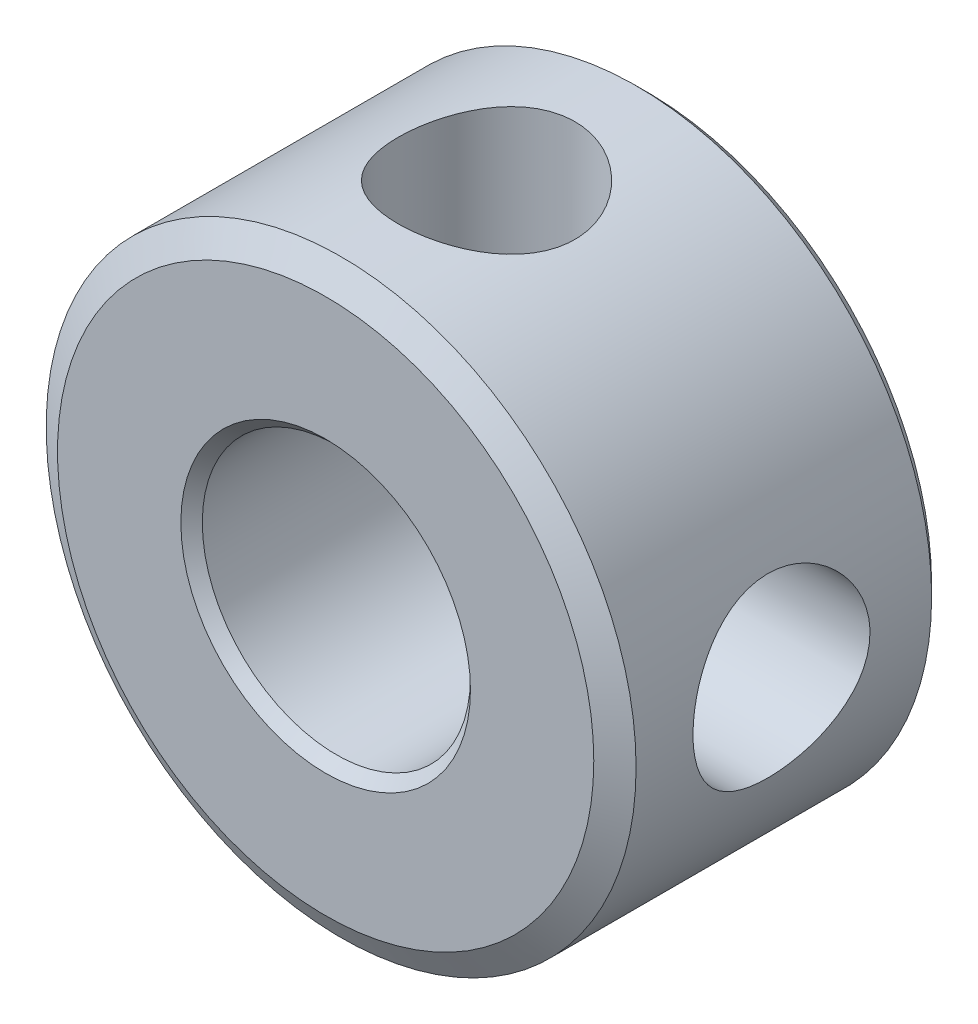
SolidWorks part; units mm, degrees
ref_plane "Front Plane" through (0, 0, 0) normal (0, 0, 1) x (1, 0, 0)
ref_plane "Top Plane" through (0, 0, 0) normal (0, 1, 0) x (1, 0, 0)
ref_plane "Right Plane" through (0, 0, 0) normal (1, 0, 0) x (0, 0, -1)
sketch "Sketch1" plane through (0, 0, 0) normal (1, 0, 0) x (0, 0, -1)
  line L0 (0, 0) -> (6, 0) construction
  line L1 (0, 5.5) -> (6, 5.5)
  line L3 (0, 2.5) -> (6, 2.5)
  line L4 (6, 5.5) -> (6, 2.5)
  line L5 (0, 2.5) -> (0, 5.5)
  dimension "D" = 5
  dimension "D1." = 11
  dimension "B" = 6
revolve "Revolve1" add sketch "Sketch1" angle 360 about L0
ref_plane "Plane1" through (0, 5.5, 0) normal (0, 1, 0) x (1, 0, 0)
hole_wizard "Tapped Hole1" positions "Sketch3" profile "Sketch2" tap size "M4x0.7" standard "JIS"
sketch "Sketch3" plane through (0, 5.5, 0) normal (0, 1, 0) x (1, 0, 0)
  line L2 (5.5, 6) -> (-5.5, 6) construction
  point P0 (0, 3)
sketch "Sketch2" plane through (0, 5.5, -3) normal (1, 0, 0) x (0, 0, 1)
  line L0 (0, 0) -> (0, 3)
  line L1 (0, 3) -> (1.65, 3)
  line L2 (1.65, 3) -> (1.65, 0)
  line L5 (1.65, 0) -> (0, 0)
  line L11 (0, 0) -> (0, 3) construction
  dimension "Thru Tap Drill Dia." = 3.3
  dimension "Thru Tap Drill Depth" = 3
cosmetic thread "Hole Thread2" parameters "M"=4
pattern_circular "CirPattern1" count 2 every 90 about axis through (0, 0, 0) along (0, 0, 1) of "Tapped Hole1"
chamfer "Chamfer1" distance 0.2 3 edges at (5.5, 0, -6) (2.5, 0, 0) (2.5, 0, -6)
sketch "Sketch4" plane through (0, 0, 0) normal (1, 0, 0) x (0, 0, -1)
  line L1 (0.2887, 5.5) -> (0, 5)
  line L3 (0, 5.5) -> (6, 5.5) construction
  line L4 (0.2887, 5.5) -> (0, 5.5)
  line L5 (0, 0) -> (6, 0) construction
  line L6 (6, -5.5) -> (6, 5.5) construction
  line L7 (0, 2.5) -> (0, 5.5) construction
  line L8 (0, 5.5) -> (0, 5)
  dimension "D1_s" = 10
  dimension "D1" = 30
revolve "Cut-Revolve1" cut sketch "Sketch4" angle 360 about L5
sketch "Sketch5" [suppressed] plane through (0, 0, 0) normal (1, 0, 0) x (0, 0, -1)
  line L0 (0, 5.5) -> (0, 5)
  line L1 (0, 5.5) -> (0, -5.5) construction
  line L2 (0, 5) -> (0.2887, 5.5)
  line L5 (0, 0) -> (8, 0) construction
  line L6 (8, -5.3) -> (8, 5.3) construction
  line L7 (0.2887, 5.5) -> (0, 5.5)
  dimension "D1" = 30
  dimension "D1_s" = 10
  dimension "D1." = 11
revolve "Cut-Revolve2" [suppressed] cut sketch "Sketch5" angle 360 about L5
equation "\"D1@Sketch3\"= \"B@Sketch1\" / 2"
equation "\"Cut-Revolve1\" = if ( \"D1.@Sketch1\" = \"D1_s@Sketch4\" , \"suppressed\" , \"unsuppressed\" )"
equation "\"Plane dim\"= \"D1.@Sketch1\" * 0.5"
